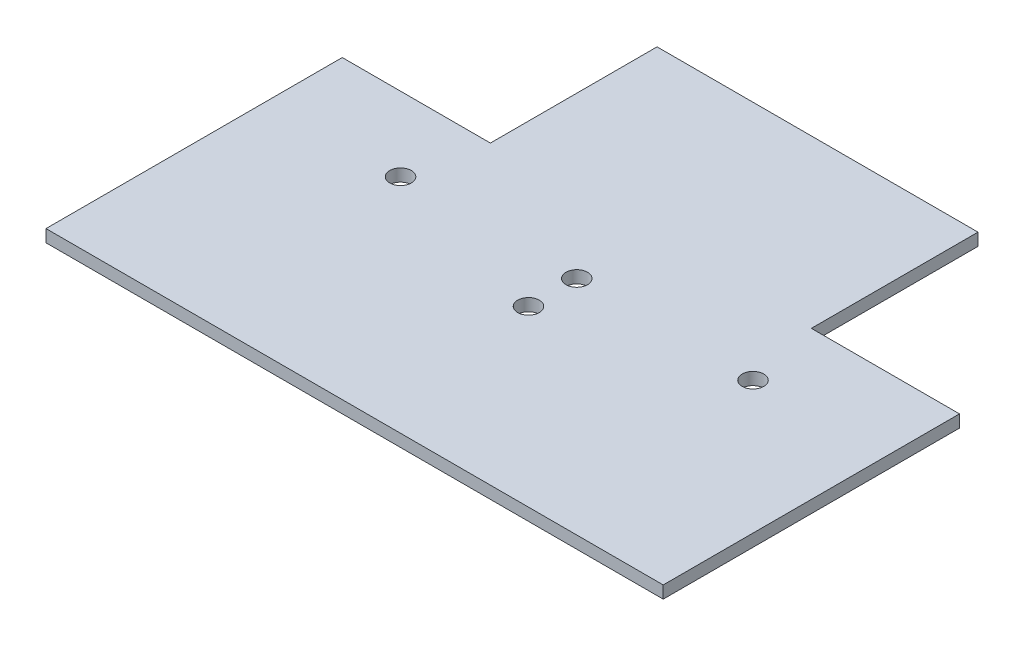
SolidWorks part; units mm, degrees
ref_plane "Alzado" through (0, 0, 0) normal (0, 0, 1) x (1, 0, 0)
ref_plane "Planta" through (0, 0, 0) normal (0, 1, 0) x (1, 0, 0)
ref_plane "Vista lateral" through (0, 0, 0) normal (1, 0, 0) x (0, 0, -1)
sketch "Croquis1" plane through (0, 0, 0) normal (0, 1, 0) x (1, 0, 0)
  line L0 (-50, 10.5) -> (-26, 10.5)
  line L1 (-50, 37.5) -> (50, 37.5)
  line L2 (-50, 37.5) -> (-50, -37.5)
  line L3 (-50, -37.5) -> (50, -37.5)
  line L4 (50, 37.5) -> (50, -37.5)
  line L5 (-50, 37.5) -> (50, -37.5) construction
  line L6 (-50, -37.5) -> (50, 37.5) construction
  line L7 (-26, 10.5) -> (-26, 37.5)
  line L8 (0, 0) -> (0, -18.4798) construction
  line L9 (26, 10.5) -> (26, 37.5)
  line L10 (50, 10.5) -> (26, 10.5)
  circle A0 centre (28.55, -1.5041) radius 1.75
  circle A1 centre (-28.55, -1.5041) radius 1.75
  circle A2 centre (0, -1.5041) radius 1.75
  circle A3 centre (0, -9.3293) radius 1.75
  point P0 (0, 0)
  dimension "D5" = 3.5
  dimension "D6" = 3.5
  dimension "D7" = 3.5
  dimension "D8" = 3.5
  dimension "D1" = 75
  dimension "D2" = 100
  dimension "D3" = 27
  dimension "D4" = 24
extrude "Saliente-Extruir1" add sketch "Croquis1" along normal blind 2 contours L4 L10 L9 L1 L7 L0 L2 L3
